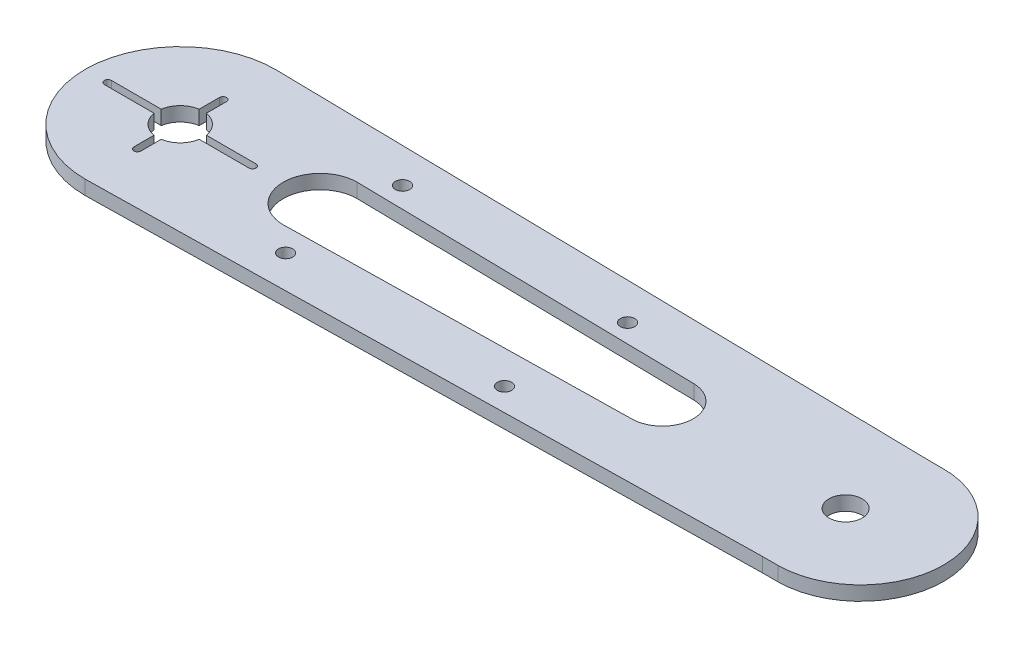
SolidWorks part; units mm, degrees
ref_plane "Front Plane" through (0, 0, 0) normal (0, 0, 1) x (1, 0, 0)
ref_plane "Top Plane" through (0, 0, 0) normal (0, 1, 0) x (1, 0, 0)
ref_plane "Right Plane" through (0, 0, 0) normal (1, 0, 0) x (0, 0, -1)
sketch "Sketch1" plane through (0, 0, 0) normal (0, 1, 0) x (1, 0, 0)
  line L0 (0.3571, 19.9968) -> (140.3125, 17.4972)
  line L1 (140, -17.5) -> (0, -20)
  circle A0 centre (0, 0) radius 20
  circle A1 centre (140, 0) radius 17.5
  point P11 (70.9941, 1.1797)
  dimension "D1" = 140
  dimension "D2" = 40
  dimension "D3" = 35
extrude "Boss-Extrude1" add sketch "Sketch1" along normal blind 3 contours L1 A0 | A1 L0 A0 L1 | A1 A0
sketch "Sketch2" plane through (0, 3, 0) normal (0, 1, 0) x (1, 0, 0)
  circle A0 centre (0, 0) radius 4.8
  circle A1 centre (140, 0) radius 3.375
  dimension "D1" = 9.6
  dimension "D2" = 6.75
extrude "Cut-Extrude1" cut sketch "Sketch2" against normal through all
sketch "Sketch4" plane through (0, 3, 0) normal (0, 1, 0) x (1, 0, 0)
  line L0 (101.2839, 6.7707) -> (29.173, 8.0586)
  line L1 (29.1576, -7.4774) -> (101.4946, -6.1857)
  arc A6 (29.173, 8.0586) -> (29.1576, -7.4774) centre (29.1653, 0.2906) ccw
  arc A7 (101.2839, 6.7707) -> (101.0524, -6.1936) centre (101.1578, 0.2888) cw
  dimension "D2" = 7.768
  dimension "D3" = 6.4832
  dimension "D1" = 72.337
  dimension "D4" = 2.046
extrude "Cut-Extrude3" cut sketch "Sketch4" against normal through all contours A7 L0 A6 L1
sketch "Sketch5" plane through (0, 3, 0) normal (0, 1, 0) x (1, 0, 0)
  line L0 (0, 0) -> (140, 0) construction
  line L1 (70, 31.2057) -> (70, -26.0603) construction
  circle A1 centre (0, 6.9681) radius 0.5
  circle A2 centre (-9.27, 0.0472) radius 0.5
  circle A3 centre (0, -7.7251) radius 0.5
  circle A4 centre (9.9339, 0) radius 0.5
  dimension "D3" = 1
  dimension "D4" = 9.27
  dimension "D1" = 140
  dimension "D2" = 70
sketch "Sketch6" plane through (0, 0, 0) normal (0, 1, 0) x (1, 0, 0)
  line L0 (-15.22, 0) -> (15.22, 0) construction
  line L1 (0, 0) -> (140, 0) construction
  line L2 (-15.22, 0.75) -> (15.22, 0.75)
  line L3 (-15.22, -0.75) -> (15.22, -0.75)
  line L4 (0, -9) -> (0, 9) construction
  line L5 (-0.75, -9) -> (-0.75, 9)
  line L6 (0.75, -9) -> (0.75, 9)
  arc A0 (-15.22, 0.75) -> (-15.22, -0.75) centre (-15.22, 0) ccw
  arc A1 (15.22, -0.75) -> (15.22, 0.75) centre (15.22, 0) ccw
  arc A2 (-0.75, -9) -> (0.75, -9) centre (0, -9) ccw
  arc A3 (0.75, 9) -> (-0.75, 9) centre (0, 9) ccw
  point P5 (0, 0)
  point P11 (0, 0)
  dimension "D1" = 0.75
  dimension "D2" = 0.75
  dimension "D3" = 30.44
  dimension "D4" = 18
extrude "Cut-Extrude4" cut sketch "Sketch6" along normal through all contours L2 A0 L3 L5 | L6 A3 L5 L2 | L5 A2 L6 L3
sketch "Sketch7" plane through (0, 3, 0) normal (0, 1, 0) x (1, 0, 0)
  line L0 (155.22, 0) -> (124.78, 0) construction
  line L1 (0, 0) -> (140, 0) construction
  line L2 (155.22, -0.5) -> (124.78, -0.5)
  line L3 (155.22, 0.5) -> (124.78, 0.5)
  line L4 (140, -6.855) -> (140, 6.855) construction
  line L5 (139.5, -6.855) -> (139.5, 6.855)
  line L6 (140.5, -6.855) -> (140.5, 6.855)
  arc A0 (155.22, -0.5) -> (155.22, 0.5) centre (155.22, 0) ccw
  arc A1 (124.78, 0.5) -> (124.78, -0.5) centre (124.78, 0) ccw
  arc A2 (139.5, -6.855) -> (140.5, -6.855) centre (140, -6.855) ccw
  arc A3 (140.5, 6.855) -> (139.5, 6.855) centre (140, 6.855) ccw
  point P5 (140, 0)
  point P11 (140, 0)
  dimension "D1" = 0.5
  dimension "D2" = 0.5
  dimension "D3" = 30.44
  dimension "D4" = 13.71
sketch "Sketch8" plane through (0, 3, 0) normal (0, 1, 0) x (1, 0, 0)
  circle A0 centre (0, 0) radius 3.5
  circle A1 centre (140, 0) radius 3.5
  dimension "D1" = 7
  dimension "D2" = 7
extrude "Cut-Extrude6" cut sketch "Sketch8" against normal through all
sketch "Sketch12" plane through (0, 3, 0) normal (0, 1, 0) x (1, 0, 0)
  circle A1 centre (83.1946, 10.9224) radius 1.5 construction
  circle A7 centre (34.5417, 12.2315) radius 1.5 construction
  circle A9 centre (83.1946, 10.9224) radius 1.5
  circle A11 centre (34.5417, 12.2315) radius 1.5
  circle A12 centre (34.5417, -12.3733) radius 1.5
  circle A13 centre (81.8715, -13.6467) radius 1.5
  dimension "D1" = 3
  dimension "D2" = 3
  dimension "D3" = 3
  dimension "D4" = 3
extrude "Cut-Extrude8" cut sketch "Sketch12" against normal blind 10
sketch "Sketch14" plane through (0, 3, 0) normal (0, 1, 0) x (1, 0, 0)
  line L0 (140.3125, 17.4972) -> (142.8697, 17.4972) construction
  line L1 (140.3125, 17.4972) -> (142.8697, 17.4972)
  line L2 (143.3011, -17.5) -> (140, -17.5) construction
  line L3 (143.3011, -17.5) -> (140, -17.5)
  arc A0 (143.3011, -17.5) -> (142.8697, 17.4972) centre (143.1334, -0.0008) ccw construction
  arc A1 (143.3011, -17.5) -> (142.8697, 17.4972) centre (143.1334, -0.0008) ccw
  circle A2 centre (140, 0) radius 17.5 construction
  arc A3 (140, -17.5) -> (140.3125, 17.4972) centre (140, 0) ccw
extrude "Boss-Extrude2" add sketch "Sketch14" against normal blind 3
